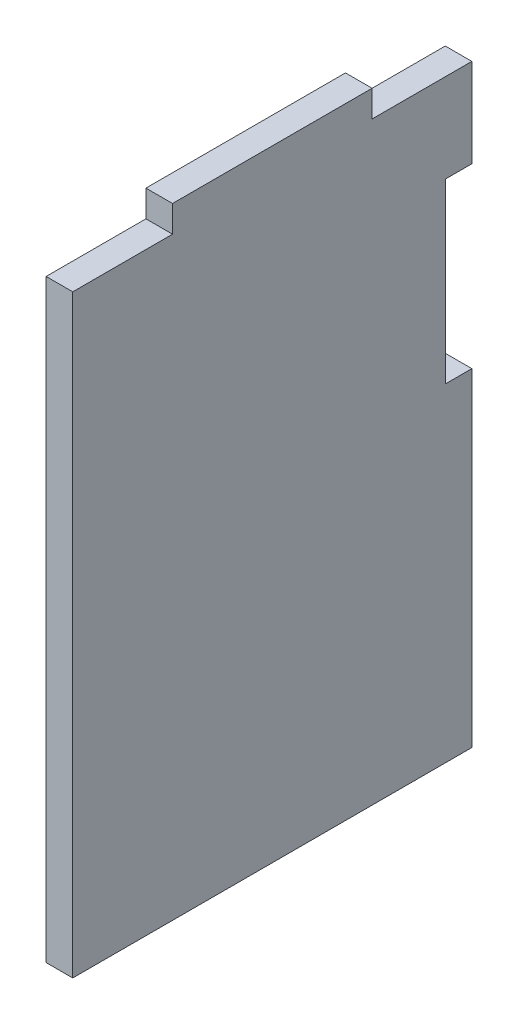
SolidWorks part; units mm, degrees
ref_plane "Front Plane" through (0, 0, 0) normal (0, 0, 1) x (1, 0, 0)
ref_plane "Top Plane" through (0, 0, 0) normal (0, 1, 0) x (1, 0, 0)
ref_plane "Right Plane" through (0, 0, 0) normal (1, 0, 0) x (0, 0, -1)
sketch "Sketch1" plane through (0, 0, 0) normal (1, 0, 0) x (0, 0, -1)
  line L1 (0, 0) -> (45, 0)
  line L2 (0, 0) -> (0, 70)
  line L3 (0, 70) -> (45, 70)
  line L4 (45, 0) -> (45, 70)
  dimension "D1" = 70
  dimension "D2" = 45
extrude "Boss-Extrude1" add sketch "Sketch1" along normal blind 3
sketch "Sketch2" plane through (3, 0, 0) normal (1, 0, 0) x (0, 0, -1)
  line L0 (45, 0) -> (45, 70) construction
  line L1 (45, 70) -> (33.75, 70)
  line L2 (11.25, 67) -> (0, 67)
  line L3 (11.25, 67) -> (11.25, 70)
  line L4 (11.25, 70) -> (0, 70)
  line L5 (0, 67) -> (0, 70)
  line L6 (45, 70) -> (45, 67)
  line L7 (45, 67) -> (33.75, 67)
  line L8 (33.75, 70) -> (33.75, 67)
  line L9 (45, 57) -> (42, 57)
  line L10 (45, 57) -> (45, 37)
  line L11 (45, 37) -> (42, 37)
  line L12 (42, 57) -> (42, 37)
  line L13 (45, 70) -> (0, 70) construction
  dimension "D1" = 11.25
  dimension "D2" = 3
  dimension "D3" = 3
  dimension "D4" = 11.25
  dimension "D5" = 3
  dimension "D6" = 20
  dimension "D7" = 13
extrude "Cut-Extrude1" cut sketch "Sketch2" against normal blind 10
